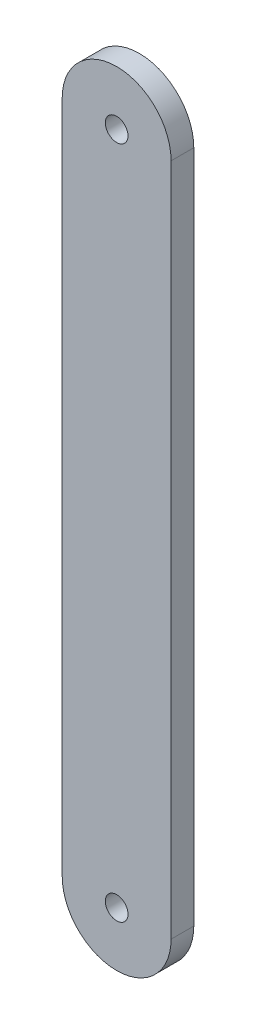
SolidWorks part; units mm, degrees
ref_plane "前视基准面" through (0, 0, 0) normal (0, 0, 1) x (1, 0, 0)
ref_plane "上视基准面" through (0, 0, 0) normal (0, 1, 0) x (1, 0, 0)
ref_plane "右视基准面" through (0, 0, 0) normal (1, 0, 0) x (0, 0, -1)
ref_plane "基准面4" through (0, 0, 5) normal (0, 0, 1) x (1, 0, 0)
sketch "草图1" plane through (0, 0, 5) normal (0, 0, 1) x (1, 0, 0)
  line L0 (12, -74.28) -> (12, 74.28)
  line L1 (-12, 74.28) -> (-12, -74.28)
  circle A0 centre (0, -74.28) radius 2.5
  circle A1 centre (0, 74.28) radius 2.5
  arc A2 (12, 74.28) -> (-12, 74.28) centre (0, 74.28) ccw
  arc A3 (-12, -74.28) -> (12, -74.28) centre (0, -74.28) ccw
  dimension "D1" = 5
  dimension "D2" = 5
extrude "凸台-拉伸1" add sketch "草图1" against normal blind 5
